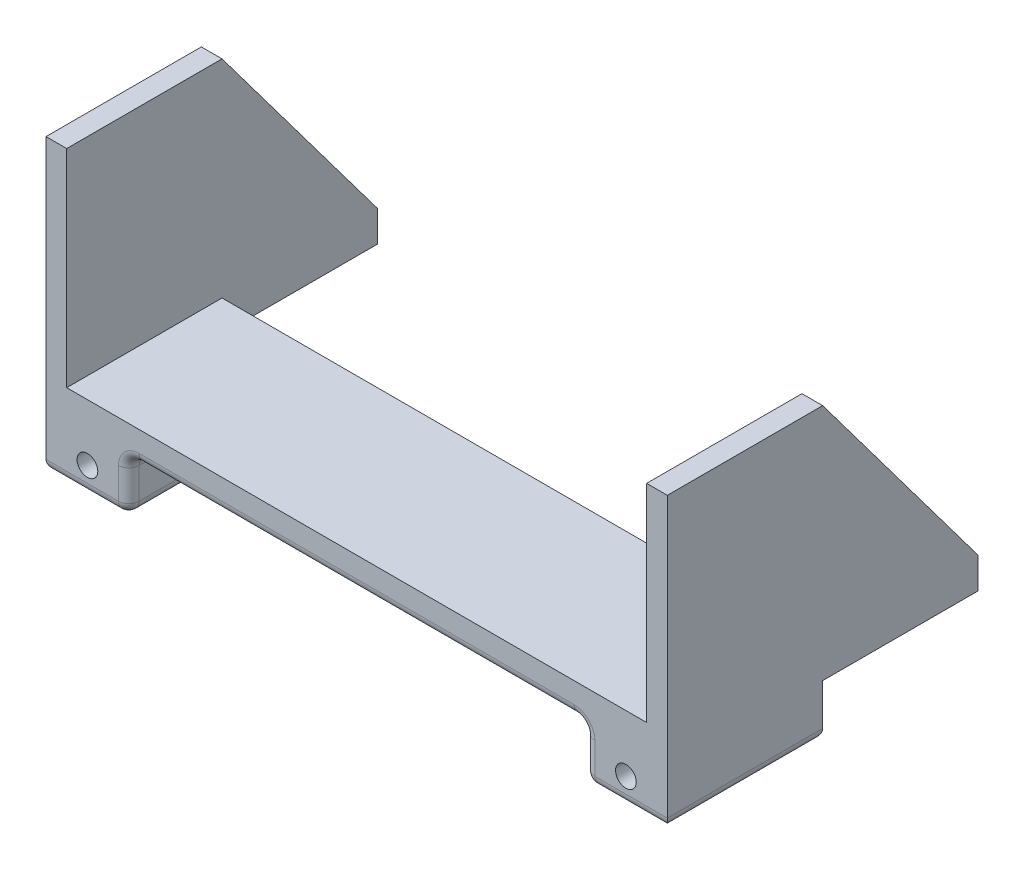
SolidWorks part; units mm, degrees
ref_plane "Front Plane" through (0, 0, 0) normal (0, 0, 1) x (1, 0, 0)
ref_plane "Top Plane" through (0, 0, 0) normal (0, 1, 0) x (1, 0, 0)
ref_plane "Right Plane" through (0, 0, 0) normal (1, 0, 0) x (0, 0, -1)
sketch "Эскиз1" plane through (0, 0, 0) normal (0, 0, 1) x (1, 0, 0)
  line L0 (0, 34.6008) -> (0, -64.6008) construction
  line L1 (-300, 0) -> (89.6614, 0) construction
  line L2 (-300, -15) -> (-300, 0)
  line L3 (-280, 15) -> (280, 15)
  line L4 (0, 15) -> (0, -15)
  line L5 (300, -15) -> (-300, -15)
  line L6 (-300, 0) -> (-300, 215)
  line L7 (-300, 215) -> (-280, 215)
  line L8 (-280, 215) -> (-280, 15)
  line L9 (280, 215) -> (280, 15)
  line L10 (300, 215) -> (280, 215)
  line L11 (300, 0) -> (300, 215)
  line L12 (300, -15) -> (300, 0)
  point P5 (0, 0)
  point P18 (-290, 0.2825)
  dimension "D1" = 30
  dimension "D2" = 20
  dimension "D3" = 300
  dimension "D4" = 200
extrude "Бобышка-Вытянуть1" add sketch "Эскиз1" along normal blind 300 contours L3 L9 L10 L11 L12 L5 L2 L6 L7 L8
sketch "Эскиз2" plane through (-280, 0, 0) normal (1, 0, 0) x (0, 0, -1)
  line L0 (-300, 15) -> (0, 15)
  line L1 (0, 15) -> (-150, 215)
  line L2 (-300, 215) -> (0, 215) construction
  line L3 (-150, 215) -> (-300, 215)
  line L4 (-300, 215) -> (-300, 15)
  line L5 (-150, 215) -> (0, 215)
  line L6 (0, 215) -> (0, 15)
  line M1 (0, 15) -> (0, 215)
  line M2 (0, 215) -> (-300, 215)
extrude "Вырез-Вытянуть1" cut sketch "Эскиз2" against normal through all both and the other way through all contours L1 M1 M2
sketch "Эскиз3" plane through (0, 15, 0) normal (0, 1, 0) x (1, 0, 0)
  line L0 (-280, -150) -> (-280, 0)
  line L1 (-280, -300) -> (-280, 0) construction
  line L2 (-280, 0) -> (280, 0)
  line L3 (280, 0) -> (280, -150)
  line L4 (280, -150) -> (-280, -150)
extrude "Вырез-Вытянуть2" cut sketch "Эскиз3" against normal through all
sketch "Эскиз4" plane through (0, -15, 0) normal (0, -1, 0) x (1, 0, 0)
  line L0 (-300, 300) -> (300, 300)
  line L1 (300, 300) -> (300, 150)
  line L2 (300, 300) -> (300, 0) construction
  line L3 (300, 150) -> (-300, 150)
  line L4 (-300, 150) -> (-300, 300)
  line L5 (-300, 300) -> (-220, 300)
  line L6 (-220, 300) -> (-220, 150)
  line L7 (-220, 150) -> (-300, 150)
  line L8 (220, 300) -> (220, 150)
  line M8 (-280, 150) -> (280, 150)
  line M11 (300, 0) -> (300, 300)
  line M12 (300, 300) -> (-300, 300)
  line M13 (-300, 300) -> (-300, 0)
  dimension "D1" = 80
  dimension "D2" = 80
extrude "Бобышка-Вытянуть2" add sketch "Эскиз4" along normal blind 50 contours L6 L0 L3 M13 M8 | L8 L3 M12 M8 M11
fillet "Скругление1" radius 10 16 edges at (0, -15, 150) (0, -15, 300) (300, -65, 225) (260, -65, 300) (260, -65, 150) (220, -40, 300) (220, -65, 225) (220, -40, 150) (220, -15, 225) (-220, -40, 300) (-220, -40, 150) (-220, -15, 225) (-260, -65, 300) (-260, -65, 150) (-300, -65, 225) (-220, -65, 225)
sketch "Эскиз5" plane through (0, 0, 300) normal (0, 0, 1) x (1, 0, 0)
  line L0 (0, 276.9787) -> (0, -182.1242) construction
  line L1 (-260, 276.9787) -> (-260, -182.1242) construction
  line L2 (-378.0456, -40) -> (-160.1213, -40) construction
  line L3 (-230, -65) -> (-290, -65) construction
  circle A0 centre (-260, -40) radius 10
  circle A1 centre (260, -40) radius 10
  point P9 (-260, -40)
  point P14 (0, 0)
  dimension "D3" = 20
  dimension "D1" = 260
  dimension "D2" = 25
extrude "Вырез-Вытянуть3" cut sketch "Эскиз5" against normal through all both and the other way through all
